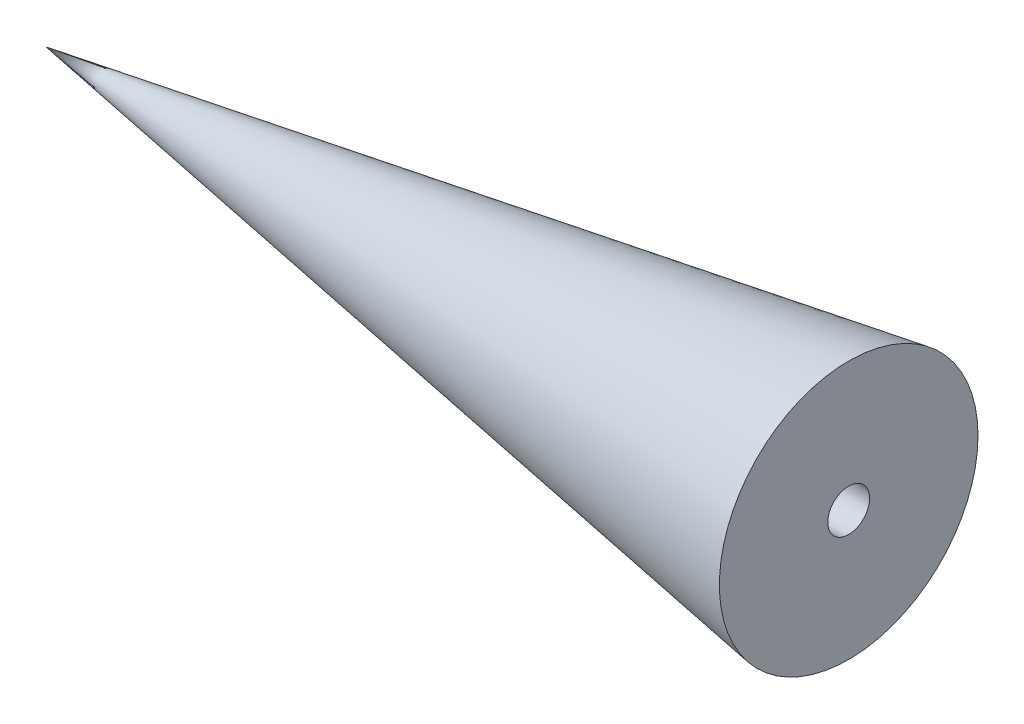
SolidWorks part; units mm, degrees
material "6063-T1"
ref_plane "Płaszczyzna przednia" through (0, 0, 0) normal (0, 0, 1) x (1, 0, 0)
ref_plane "Płaszczyzna górna" through (0, 0, 0) normal (0, 1, 0) x (1, 0, 0)
ref_plane "Płaszczyzna prawa" through (0, 0, 0) normal (1, 0, 0) x (0, 0, -1)
sketch "Sketch1" plane through (0, 0, 0) normal (0, 0, 1) x (1, 0, 0)
  line L1 (0, 0) -> (0, 18.525)
  line L2 (0, 18.525) -> (-115, 0)
  line L3 (0, 0) -> (-115, 0) construction
  line L4 (0, 0) -> (-115, 0)
  dimension "D1" = 115
  dimension "D2" = 18.525
revolve "Revolve1" add sketch "Sketch1" angle 360 about L3
sketch "Sketch2" plane through (0, 0, 0) normal (1, 0, 0) x (0, 0, -1)
  circle A0 centre (0, 0) radius 3
  dimension "D1" = 6
extrude "Cut-Extrude1" cut sketch "Sketch2" against normal blind 50
sketch "Sketch3" plane through (0, 0, 0) normal (1, 0, 0) x (0, 0, -1)
  circle A0 centre (0, 0) radius 6.8454
  circle A1 centre (0, 0) radius 10.2081
